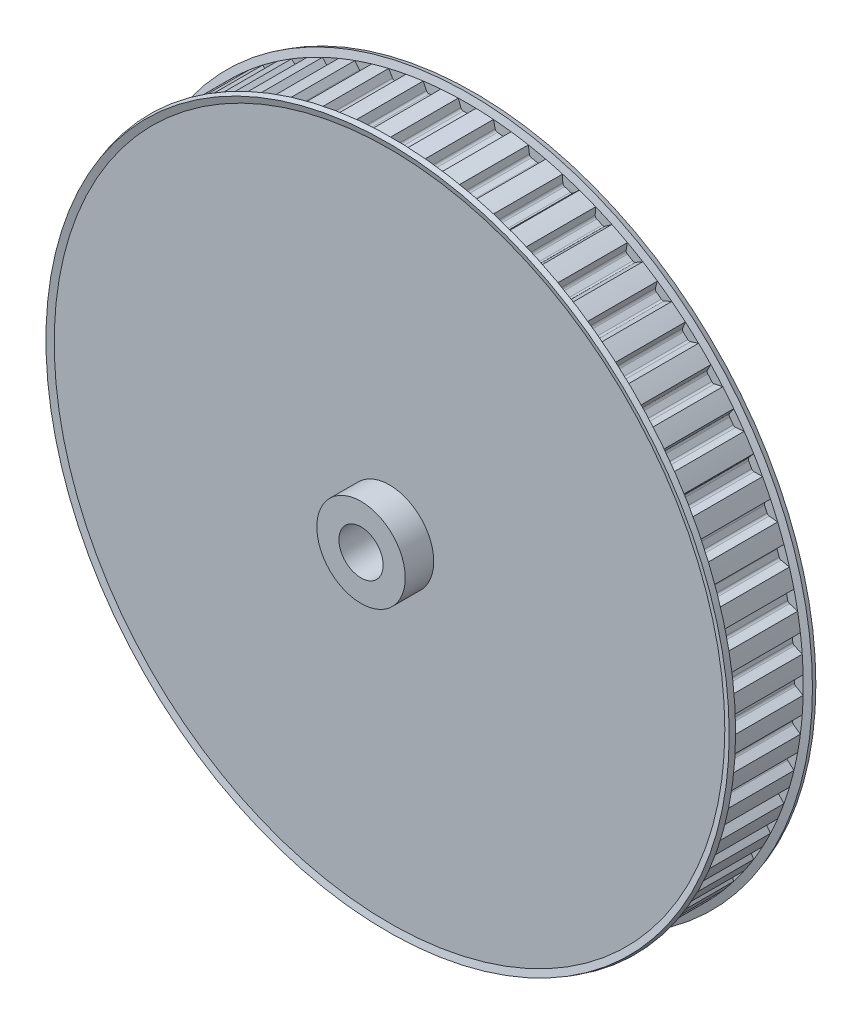
SolidWorks part; units mm, degrees
extrude "BasePulley" add sketch "Sketch1" against normal blind 10.414
sketch "Sketch1" plane through (0, 0, 0) normal (0, 0, 1) x (1, 0, 0)
  circle A0 centre (0, 0) radius 48.26
  dimension "Outside_dia" = 96.52
revolve "Flange" add sketch "Sketch2" angle 360 about L11
sketch "Sketch2" plane through (0, 0, 0) normal (1, 0, 0) x (0, 0, -1)
  line L0 (10.414, 48.26) -> (10.7246, 49.276)
  line L1 (10.7246, 49.276) -> (11.429, 49.0606)
  line L2 (5.207, 0) -> (5.207, 66.675) construction
  line L3 (11.429, 49.0606) -> (11.1506, 48.1499)
  line L4 (11.1506, 48.1499) -> (11.1506, 0)
  line L5 (0, 48.26) -> (-0.3106, 49.276)
  line L6 (10.414, -48.26) -> (10.414, 48.26) construction
  line L7 (-0.3106, 49.276) -> (-1.015, 49.0606)
  line L8 (-1.015, 49.0606) -> (-0.7366, 48.1499)
  line L9 (-0.7366, 48.1499) -> (-0.7366, 0)
  line L10 (10.414, 48.26) -> (0, 48.26)
  line L11 (0, 0) -> (38.2092, 0) construction
  line L12 (10.414, 0) -> (0, 0) construction
  line L13 (-0.7366, 0) -> (11.1506, 0)
  dimension "D1" = 5.207
  dimension "Flange_ang" = 17
  dimension "D3" = 0.7366
  dimension "D2" = 48.26
  dimension "Flange_ht" = 1.016
ref_plane "Plane1" through (0, 0, 0) normal (0, 0, 1) x (1, 0, 0)
ref_plane "Plane2" through (0, 0, 0) normal (0, 1, 0) x (1, 0, 0)
ref_plane "Plane3" through (0, 0, 0) normal (1, 0, 0) x (0, 0, -1)
sketch "Clipboard" plane through (0, 0, 0) normal (0, 0, 1) x (1, 0, 0)
  line L0 (0, 0) -> (6.604, 0)
  line L1 (0, 0) -> (7.62, 13.1982)
  line L2 (0, 0) -> (7.62, -13.1982)
ref_plane "Plane4" through (0, 0, -5.207) normal (0, 0, 1) x (1, 0, 0)
sketch "Sketch3" plane through (0, 0, -5.207) normal (0, 0, 1) x (1, 0, 0)
  line L0 (-1.2827, 48.26) -> (-1.2827, 73.66)
  line L1 (1.2827, 48.26) -> (1.2827, 73.66)
  line L2 (0, 0) -> (0, 48.26) construction
  line L3 (-1.2827, 48.26) -> (1.2827, 48.26) construction
  line L4 (-0.5537, 46.99) -> (0.3295, 46.99)
  line L5 (1.2827, 48.26) -> (0.6595, 47.1805)
  line L6 (-1.2827, 48.26) -> (-0.9117, 47.2407)
  line L7 (1.2827, 73.66) -> (-1.2827, 73.66)
  arc A0 (0.3295, 46.99) -> (0.6595, 47.1805) centre (0.3295, 47.371) ccw
  arc A2 (-0.9117, 47.2407) -> (-0.5537, 46.99) centre (-0.5537, 47.371) ccw
  dimension "Grv_rad_bot" = 0.381
  dimension "Grv_ang" = 50
  dimension "D3" = 20
  dimension "Grv_width" = 2.5654
  dimension "D4" = 25.4
  dimension "D1" = 48.26
  dimension "Grv_depth" = 1.27
extrude "Groove" cut sketch "Sketch3" against normal mid plane 10.414
pattern_circular "Grooves" count 60 every 6 about axis through (0, 0, -10.414) along (0, 0, 1) of "Groove"
sketch "Sketch4" plane through (0, 0, 0) normal (1, 0, 0) x (0, 0, -1)
  line L0 (0, 0) -> (47.6781, 0) construction
  line L1 (10.414, 0) -> (0, 0) construction
  line L2 (0, 0) -> (-4.826, 0)
  line L3 (-4.826, 0) -> (-4.826, 6.35)
  line L4 (-4.826, 6.35) -> (0, 6.35)
  line L5 (0, 6.35) -> (0, 0)
  line L6 (-4.826, -6.35) -> (0, -6.35) construction
revolve "BaseHub" add sketch "Sketch4" angle 360 about L0
sketch "BorSke" plane through (0, 0, 4.826) normal (0, 0, 1) x (1, 0, 0)
  circle A0 centre (0, 0) radius 3.175
extrude "Bore" cut sketch "BorSke" against normal through all
sketch "KeySke" plane through (0, 0, 4.826) normal (0, 0, 1) x (1, 0, 0)
  line L0 (0.127, 3.429) -> (0.127, 0)
  line L1 (0.127, 3.429) -> (-0.127, 3.429)
  line L2 (-0.127, 3.429) -> (-0.127, 0)
  line L3 (-0.127, 0) -> (0.127, 0)
  line L4 (0, 31.75) -> (0, -3.175) construction
  dimension "Width" = 10.414
extrude "Keyway" [suppressed] cut sketch "KeySke" against normal through all
pattern_circular "Keyway2" [suppressed] count 2 every 90
equation "\"D1@Plane4\" = \"Width@BasePulley\" / 2"
equation "\"D1@Groove\" = \"Width@BasePulley\""
equation "\"D1@Sketch3\" = \"Outside_dia@Sketch1\" / 2"
equation "\"D1@Sketch2\" = \"Width@BasePulley\" / 2"
equation "\"D2@Sketch2\" = \"Outside_dia@Sketch1\" / 2"
equation "\"D3@Sketch2\" = \"Flange_thickness@Sketch2\""
equation "\"Num_grvs@Clipboard\" = int( \"Num_grvs@Clipboard\" )"
equation "\"Show_grvs@Clipboard\" = int( \"Show_grvs@Clipboard\" )"
equation "\"Show_grvs@Clipboard\" = ((sgn( \"Show_grvs@Clipboard\" - \"Num_grvs@Clipboard\" )-1)*( \"Show_grvs@Clipboard\" - \"Num_grvs@Clipboard\" ))/-2+ \"Num_grvs@Clipboard\""
equation "\"Show_grvs@Clipboard\" = ((sgn( \"Show_grvs@Clipboard\" - 1.0)+1)*( \"Show_grvs@Clipboard\" - 1.0))/2 +1.0"
equation "\"Angle@Grooves\" = 360.0 / \"Num_grvs@Clipboard\""
equation "\"Num_grvs@Grooves\" =  \"Show_grvs@Clipboard\""
equation "\"Offset@KeySke\" = \"T_dim@Clipboard\" - \"Diameter@BorSke\" / 2.0"
equation "\"OAL@Clipboard\" = \"Overall_len@Clipboard\""
equation "\"Hub_depth@Sketch4\" = \"OAL@Clipboard\" - \"Width@BasePulley\""
